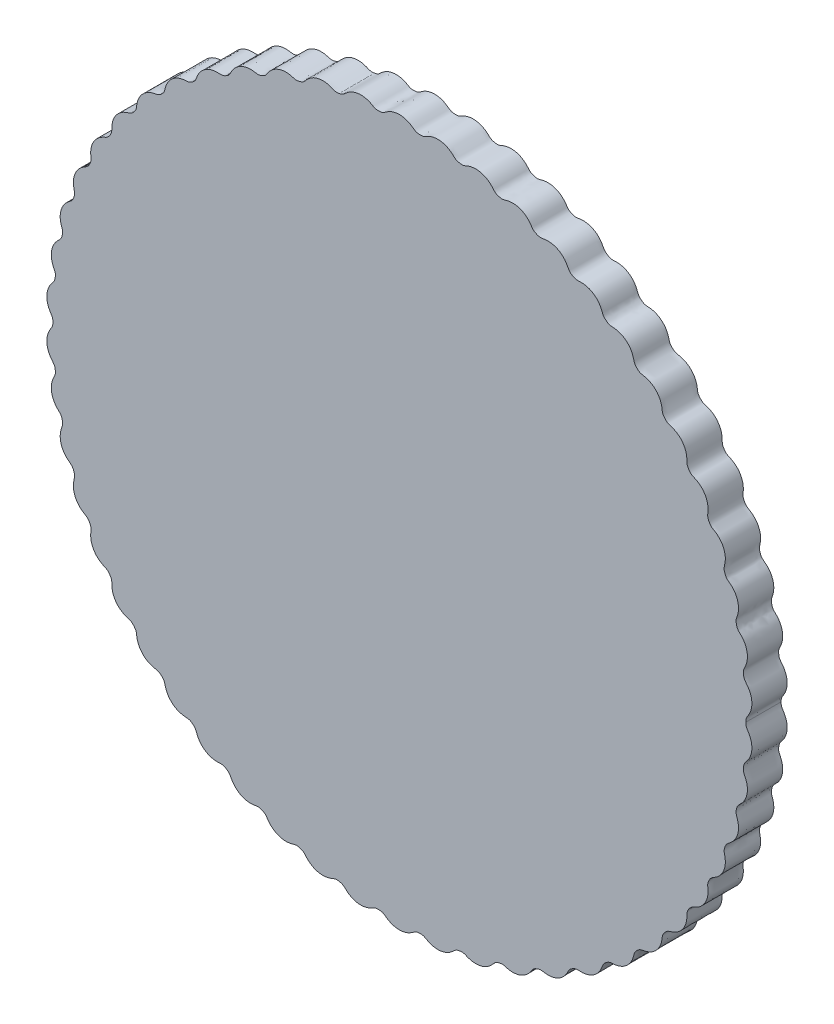
SolidWorks part; units mm, degrees
ref_plane "Front Plane" through (0, 0, 0) normal (0, 0, 1) x (1, 0, 0)
ref_plane "Top Plane" through (0, 0, 0) normal (0, 1, 0) x (1, 0, 0)
ref_plane "Right Plane" through (0, 0, 0) normal (1, 0, 0) x (0, 0, -1)
other "Configuration Table"
sketch "Sketch2" plane through (0, 0, 0) normal (0, 0, 1) x (1, 0, 0)
  line L0 (-196.3825, 0) -> (196.3825, 0) construction
  spline S0 degree 4 number of poles 653 (192.1981, -55.0151) -> (-192.1981, -55.0151) construction
  spline S1 degree 4 number of poles 544 (196.3825, 0) -> (-196.3825, 0)
  spline S2 degree 4 number of poles 653 (-192.1981, 55.0151) -> (192.1981, 55.0151) construction
  spline S3 degree 4 number of poles 544 (-196.3825, 0) -> (196.3825, 0)
  dimension "D1" = 392.765
extrude "Boss-Extrude1" add sketch "Sketch2" along normal blind 20
equation "\"Z_b\" = 54'齿数"
equation "\"Z_p\"= \"Z_b\" + 1'针齿数"
equation "\"R_z\" = 0.2m'针齿中心圆半径"
equation "\"A\" = 0.003m'偏心距"
equation "\"R_rp\" = 0.00325m'针齿半径"
equation "\"K\"= \"A\" * \"Z_b\" / \"R_z\"'短幅系数"
equation "\"C1\"= \"K\" * 2 + 1"
equation "\"C2\"= \"K\" * 2"
equation "\"b\" = 0.02m"
equation "\"D1@Boss-Extrude1\"=\"b\""
